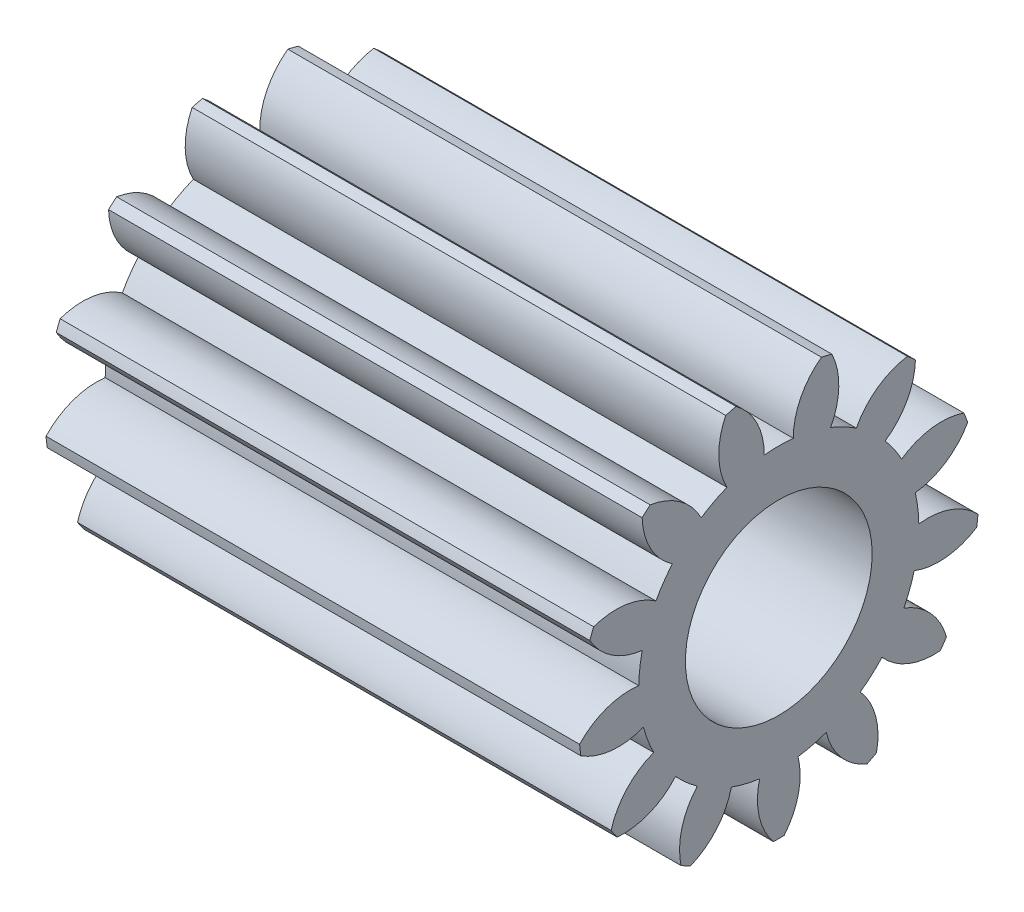
SolidWorks part; units mm, degrees
ref_plane "Plane1" through (0, 0, 0) normal (0, 0, 1) x (1, 0, 0)
ref_plane "Plane2" through (0, 0, 0) normal (0, 1, 0) x (1, 0, 0)
ref_plane "Plane3" through (0, 0, 0) normal (1, 0, 0) x (0, 0, -1)
sketch "HoldingSke" plane through (0, 0, 0) normal (0, 1, 0) x (1, 0, 0)
  line L0 (0, 0) -> (0.4872, -0.1125)
  line L1 (-15, 0) -> (100, 0) construction
  line L2 (0, 0) -> (-2.1039, 2.3779)
  line L3 (0, 0) -> (-11.863, 4.5341)
  line L4 (0, 0) -> (8.4147, 1.9427)
  line L5 (0, 0) -> (-46.8476, -17.4728)
  line L6 (0, 0) -> (-33.1585, -22.3721)
  line L7 (-2.1039, 2.3779) -> (8.6586, 51.2059)
  line L8 (-76.2, 54.61) -> (-75.9, 54.61)
  line L9 (-71.009, 38.7566) -> (-53.1078, 45.2721)
  line L10 (-76.2, 71.12) -> (104.1128, 71.12)
  line L11 (0, 0) -> (-40, 0)
  line L12 (-76.2, 101.6) -> (-76.133, 101.6)
  line L13 (24.9733, 27.94) -> (52.9518, 28.4284)
  line L14 (24.9733, 27.94) -> (24.9743, 27.94)
  line L15 (24.9733, 27.94) -> (100.4006, 29.5858)
  line L16 (-63.627, -2) -> (-12.827, -2)
  circle A0 centre (0, 0) radius 1
  circle A1 centre (0, 0) radius 10.499
  circle A2 centre (0, 0) radius 37.5
  circle A3 centre (0, 0) radius 1
  dimension "MHD" = 20.998
  dimension "Hub_dia" = 75
  dimension "Bore" = 2
  dimension "MBD" = 2
  dimension "Num_teeth" = 13
  dimension "Pitch" = 0.5
  dimension "Overall_len" = 50
  dimension "Show_teeth" = 13
  dimension "Thickness" = 40
  dimension "OAL" = 50.0001
  dimension "T_dim" = 0.3
  dimension "Ap" = 20
  dimension "H" = 19.05
  dimension "Pitch_radius" = 180.3128
  dimension "Width" = 40
  dimension "Backlash" = 0.067
  dimension "Addendum_fac" = 1
  dimension "Dedendum_fac" = 1.25
  dimension "Clearance_fac" = 0.25
  dimension "Dedendum_add" = 0.001
  dimension "Module" = 2
sketch "BasProSke" plane through (0, 0, 0) normal (0, 1, 0) x (1, 0, 0)
  line L0 (-10, 0) -> (60, 0) construction
  line L1 (0, 0) -> (0, 15)
  line L2 (0, 0) -> (40, 0)
  line L3 (40, 0) -> (40, 15)
  line L4 (40, 15) -> (0, 15)
  dimension "Thickness" = 40
  dimension "Diameter" = 30
revolve "Base-Revolve" add sketch "BasProSke" angle 360 about L0
sketch "TooCutSke" plane through (0, 0, 0) normal (1, 0, 0) x (0, 0, -1)
  line L1 (0, 0) -> (0, 107) construction
  line L2 (0, 0) -> (-1.6841, 12.8905) construction
  line L3 (0, 0) -> (-6.1834, 25.087) construction
  line L4 (-1.6841, 12.8905) -> (-3.0917, 12.5435) construction
  arc A0 (1.0882, 10.4424) -> (-1.0882, 10.4424) centre (0, 0) ccw
  arc A1 (3.2249, 14.6752) -> (-3.2249, 14.6752) centre (0, 0) ccw
  circle A2 centre (0, 0) radius 13 construction
  circle A3 centre (0, 0) radius 12.216 construction
  arc A4 (-1.0882, 10.4424) -> (-3.2249, 14.6752) centre (-6.2882, 10.4733) ccw
  arc A5 (3.2249, 14.6752) -> (1.0882, 10.4424) centre (6.2882, 10.4733) ccw
  dimension "Root_dia" = 20.998
  dimension "Overcut_dia" = 30.0508
  dimension "Pitch_dia" = 26
  dimension "Base_dia" = 24.432
  dimension "Flank_rad" = 5.2
  dimension "Half_ang" = 13.846
  dimension "Half_CT" = 1.4497
extrude "ToothCut" cut sketch "TooCutSke" along normal through all
fillet "Breaks" [suppressed] radius 0.04
fillet "RootFillets" [suppressed] radius 0.501
pattern_circular "TeethCuts" count 13 every 27.692 about axis through (-10, 0, 0) along (1, 0, 0) of "ToothCut", "RootFillets", "Breaks"
sketch "HubNeaOneSke" plane through (0, 0, 0) normal (-1, 0, 0) x (0, 0, 1)
  circle A0 centre (0, 0) radius 10.499
  dimension "Diameter" = 20.998
extrude "HubNearOne" [suppressed] add sketch "HubNeaOneSke" along normal blind 10.0001
sketch "HubNeaBotSke" plane through (0, 0, 0) normal (-1, 0, 0) x (0, 0, 1)
  circle A0 centre (0, 0) radius 10.499
  dimension "Diameter" = 20.998
extrude "HubNearBoth" [suppressed] add sketch "HubNeaBotSke" along normal blind 5
ref_plane "FarPln" through (40, 0, 0) normal (1, 0, 0) x (0, 0, -1)
sketch "HubFarSke" plane through (40, 0, 0) normal (1, 0, 0) x (0, 0, -1)
  circle A0 centre (0, 0) radius 10.499
  dimension "Diameter" = 20.998
extrude "HubFar" [suppressed] add sketch "HubFarSke" along normal blind 5
sketch "BorSke" plane through (0, 0, 0) normal (1, 0, 0) x (0, 0, -1)
  circle A0 centre (0, 0) radius 1
  dimension "Diameter" = 2
extrude "Bore" cut sketch "BorSke" along normal mid plane 100.0001
sketch "KeySke" plane through (0, 0, 0) normal (1, 0, 0) x (0, 0, -1)
  line L0 (-0.4, 0) -> (-0.4, 1.3)
  line L1 (-0.4, 1.3) -> (0.4, 1.3)
  line L2 (0.4, 1.3) -> (0.4, 0)
  line L3 (0, 0) -> (0, 34) construction
  line L4 (-0.4, 0) -> (0.4, 0)
  dimension "Offset" = 1.3
  dimension "Width" = 0.8
extrude "Keyway" [suppressed] cut sketch "KeySke" along normal mid plane 100.0001
pattern_circular "Keyway2" [suppressed] count 2 every 90 about axis through (-10, 0, 0) along (1, 0, 0)
sketch "草图2" plane through (40, 0, 0) normal (1, 0, 0) x (0, 0, -1)
  circle A0 centre (0, 0) radius 7
  dimension "D1" = 14
extrude "切除-拉伸1" cut sketch "草图2" against normal blind 17
equation "' \"Module@HoldingSke\" = 6.35"
equation "' \"Num_teeth@HoldingSke\" = 12"
equation "' \"Ap@HoldingSke\" =  20"
equation "' \"Ap@HoldingSke\" = 20"
equation "' \"Width@HoldingSke\" = 0.5 * 25.4"
equation "' \"Hub_dia@HoldingSke\"= 1 * 25.4"
equation "' \"Hub_dia@HoldingSke\" = 1 * 25.4"
equation "' \"Overall_len@HoldingSke\" = 1.0 * 25.4"
equation "' \"Bore@HoldingSke\" = 0.75 * 25.4"
equation "' \"T_dim@HoldingSke\" = 0.1 * 25.4"
equation "' \"Width@KeySke\" = 0.25 * 25.4"
equation "' \"Show_teeth@HoldingSke\" = 13"
equation "' \"Backlash@HoldingSke\" = 0.009 * 25.4"
equation "' \"Addendum_fac@HoldingSke\" = 1.0"
equation "' \"Dedendum_fac@HoldingSke\" = 1.25"
equation "' \"Dedendum_add@HoldingSke\" = 0.00005 * 25.4"
equation "' \"Clearance_fac@HoldingSke\" = 0.25"
equation "\"Pitch@HoldingSke\" = 1 / \"Module@HoldingSke\""
equation "\"Overcut_dia@TooCutSke\" = (\"Num_teeth@HoldingSke\" + 2 * \"Addendum_fac@HoldingSke\") / \"Pitch@HoldingSke\" + 0.002 * 25.4"
equation "\"Pitch_dia@TooCutSke\" = \"Num_teeth@HoldingSke\" / \"Pitch@HoldingSke\""
equation "\"Base_dia@TooCutSke\" = \"Num_teeth@HoldingSke\" / \"Pitch@HoldingSke\" * cos((\"Ap@HoldingSke\"  * 3.14159265 / 180))"
equation "\"Root_dia@TooCutSke\" = (\"Num_teeth@HoldingSke\" + 2) / \"Pitch@HoldingSke\" - 2 * (\"Addendum_fac@HoldingSke\" + \"Dedendum_fac@HoldingSke\") / \"Pitch@HoldingSke\" - \"Dedendum_add@HoldingSke\" * 2"
equation "\"Half_ang@TooCutSke\" = 180 / \"Num_teeth@HoldingSke\""
equation "\"Half_CT@TooCutSke\" = \"Num_teeth@HoldingSke\" / \"Pitch@HoldingSke\" * sin((3.14159265 / 2 / \"Num_teeth@HoldingSke\")) / 2 - 7 * \"Backlash@HoldingSke\" / 4"
equation "\"Flank_rad@TooCutSke\" = \"Num_teeth@HoldingSke\" / \"Pitch@HoldingSke\" / 5"
equation "\"Radius@RootFillets\" = \"Clearance_fac@HoldingSke\" / \"Pitch@HoldingSke\" + \"Dedendum_add@HoldingSke\""
equation "\"Break_rad@Breaks\" = 0.02 / \"Pitch@HoldingSke\""
equation "\"Thickness@HoldingSke\" = \"Width@HoldingSke\""
equation "\"OAL@HoldingSke\" = \"Thickness@HoldingSke\""
equation "\"MHD@HoldingSke\" = (\"Num_teeth@HoldingSke\" + 2) / \"Pitch@HoldingSke\" - 2 * (\"Addendum_fac@HoldingSke\" + \"Dedendum_fac@HoldingSke\")  / \"Pitch@HoldingSke\" - \"Dedendum_add@HoldingSke\" * 2"
equation "\"MBD@HoldingSke\" = (\"Num_teeth@HoldingSke\" + 2) / \"Pitch@HoldingSke\" - 2 * (\"Addendum_fac@HoldingSke\" + \"Dedendum_fac@HoldingSke\")  / \"Pitch@HoldingSke\" - \"Dedendum_add@HoldingSke\" * 2 - 0.002 * 25.4"
equation "\"MHD@HoldingSke\" = ((sgn( \"MHD@HoldingSke\" - \"Hub_dia@HoldingSke\" )-1)*( \"MHD@HoldingSke\" - \"Hub_dia@HoldingSke\" ))/-2+ \"Hub_dia@HoldingSke\""
equation "\"MBD@HoldingSke\" = ((sgn( \"MBD@HoldingSke\" - \"Bore@HoldingSke\" )-1)*( \"MBD@HoldingSke\" - \"Bore@HoldingSke\" ))/-2+ \"Bore@HoldingSke\""
equation "\"OAL@HoldingSke\" = ((sgn( \"OAL@HoldingSke\" - \"Overall_len@HoldingSke\" )+1)*( \"OAL@HoldingSke\" - \"Overall_len@HoldingSke\" ))/2 + \"Overall_len@HoldingSke\" + 0.000002 * 25.4"
equation "\"Num_teeth@TeethCuts\" = int( \"Show_teeth@HoldingSke\" ) + 1"
equation "\"Num_teeth@TeethCuts\" = ((sgn( \"Num_teeth@TeethCuts\" - \"Num_teeth@HoldingSke\" )-1)*( \"Num_teeth@TeethCuts\" - \"Num_teeth@HoldingSke\" ))/-2+ \"Num_teeth@HoldingSke\""
equation "\"Num_teeth@TeethCuts\" = ((sgn( \"Num_teeth@TeethCuts\" - 2.0)+1)*( \"Num_teeth@TeethCuts\" - 2.0))/2 +2.0"
equation "\"Angle@TeethCuts\" = 360.0 / \"Num_teeth@HoldingSke\""
equation "\"Diameter@BasProSke\" = (\"Num_teeth@HoldingSke\" + 2 * \"Addendum_fac@HoldingSke\") / \"Pitch@HoldingSke\""
equation "\"Thickness@BasProSke\"  = \"Thickness@HoldingSke\""
equation "' \"Fillet_rad@BasProSke\" =  \"Thickness@HoldingSke\" * 0.05"
equation "' \"Fillet_rad@BasProSke\" = \"Thickness@HoldingSke\" * 0.05"
equation "\"MHD@HoldingSke\" = ((sgn( \"MHD@HoldingSke\" - \"Root_dia@TooCutSke\" )-1)*( \"MHD@HoldingSke\" - \"Root_dia@TooCutSke\" ))/-2+ \"Root_dia@TooCutSke\""
equation "\"Diameter@HubNeaOneSke\" = \"MHD@HoldingSke\""
equation "\"Length@HubNearOne\" = \"OAL@HoldingSke\" - \"Thickness@BasProSke\""
equation "\"Diameter@HubNeaBotSke\" = \"MHD@HoldingSke\""
equation "\"Length@HubNearBoth\" = ( \"OAL@HoldingSke\" - \"Thickness@BasProSke\" ) / 2.0"
equation "\"Thickness@FarPln\" = \"Thickness@BasProSke\""
equation "\"Diameter@HubFarSke\" = \"MHD@HoldingSke\""
equation "\"Length@HubFar\" = ( \"OAL@HoldingSke\" - \"Thickness@BasProSke\" ) / 2.0"
equation "\"Diameter@BorSke\" = \"MBD@HoldingSke\""
equation "\"D1@Bore\" = \"OAL@HoldingSke\" * 2.0"
equation "\"D1@Keyway\" = \"OAL@HoldingSke\" * 2.0"
equation "\"Offset@KeySke\" = \"T_dim@HoldingSke\" + \"MBD@HoldingSke\" / 2.0"
